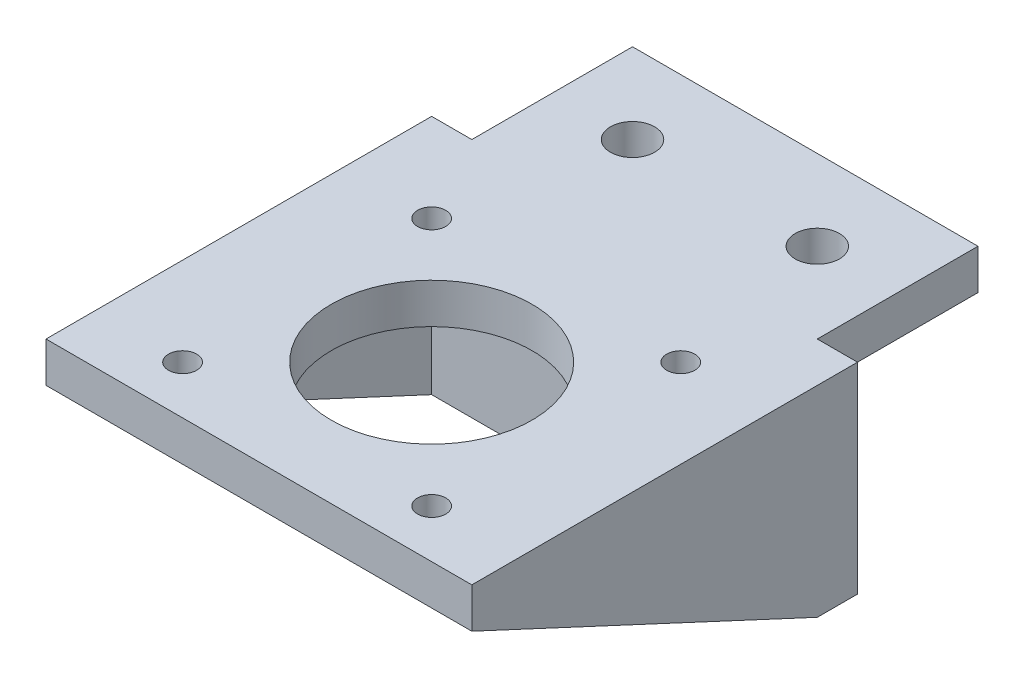
SolidWorks part; units mm, degrees
ref_plane "前视基准面" through (0, 0, 0) normal (0, 0, 1) x (1, 0, 0)
ref_plane "上视基准面" through (0, 0, 0) normal (0, 1, 0) x (1, 0, 0)
ref_plane "右视基准面" through (0, 0, 0) normal (1, 0, 0) x (0, 0, -1)
sketch "草图1" plane through (0, 0, 0) normal (0, 1, 0) x (1, 0, 0)
  line L1 (-15.1234, 10.3825) -> (27.8766, 10.3825)
  line L2 (-15.1234, 10.3825) -> (-15.1234, -32.6175)
  line L3 (-15.1234, -32.6175) -> (27.8766, -32.6175)
  line L4 (27.8766, 10.3825) -> (27.8766, -32.6175)
  line L5 (-15.1234, 10.3825) -> (27.8766, -32.6175) construction
  line L6 (-15.1234, -32.6175) -> (27.8766, 10.3825) construction
  line L11 (-9.1234, 4.3825) -> (21.8766, 4.3825) construction
  line L12 (-9.1234, 4.3825) -> (-9.1234, -26.6175) construction
  line L13 (-9.1234, -26.6175) -> (21.8766, -26.6175) construction
  line L14 (21.8766, 4.3825) -> (21.8766, -26.6175) construction
  line L15 (6.3766, -26.6175) -> (6.3766, 4.3825) construction
  line L16 (-9.1234, -11.1175) -> (21.8766, -11.1175) construction
  circle A5 centre (-9.1234, -26.6175) radius 1.75
  circle A6 centre (21.8766, -26.6175) radius 1.75
  circle A7 centre (21.8766, 4.3825) radius 1.75
  circle A8 centre (-9.1234, 4.3825) radius 1.75
  circle A9 centre (6.3766, -11.1175) radius 12.5
  point P4 (6.3766, -11.1175)
  point P5 (6.3766, -11.1175)
  point P6 (6.3766, -11.1175)
  dimension "D3" = 31
  dimension "D5" = 3.5
  dimension "D6" = 25
  dimension "D1" = 43
  dimension "D2" = 43
  dimension "D4" = 31
extrude "凸台-拉伸1" add sketch "草图1" along normal blind 5
sketch "草图2" plane through (0, 0, -10.3825) normal (0, 0, -1) x (-1, 0, 0)
  line L4 (-27.8766, 0) -> (15.1234, 0)
  line L5 (15.1234, 0) -> (15.1234, 5)
  line L6 (15.1234, 5) -> (-27.8766, 5)
  line L7 (-27.8766, 5) -> (-27.8766, 0)
  line L8 (-27.8766, 0) -> (15.1234, 0)
  line L9 (15.1234, 0) -> (15.1234, 5)
  line L10 (15.1234, 5) -> (-27.8766, 5)
  line L11 (-27.8766, 5) -> (-27.8766, 0)
  dimension "D1" = 0
extrude "凸台-拉伸2" add sketch "草图2" along normal blind 25
sketch "草图3" plane through (0, 0, 0) normal (0, -1, 0) x (1, 0, 0)
  line L0 (-15.1234, -35.3825) -> (-15.1234, 32.6175) construction
  line L1 (-15.1234, -10.3825) -> (27.8766, -10.3825)
  line L2 (-15.1234, -10.3825) -> (-15.1234, -15.3825)
  line L3 (-15.1234, -15.3825) -> (27.8766, -15.3825)
  line L4 (27.8766, -10.3825) -> (27.8766, -15.3825)
  line L5 (-15.1234, -10.3825) -> (27.8766, -15.3825) construction
  line L6 (-15.1234, -15.3825) -> (27.8766, -10.3825) construction
  line L7 (27.8766, 32.6175) -> (27.8766, -35.3825) construction
  line L8 (27.8766, -35.3825) -> (-15.1234, -35.3825) construction
  point P4 (6.3766, -12.8825)
  dimension "D1" = 20
  dimension "D2" = 5
extrude "凸台-拉伸3" add sketch "草图3" along normal blind 20
sketch "草图4" plane through (27.8766, 0, 0) normal (1, 0, 0) x (0, 0, -1)
  line L0 (-32.6175, 0) -> (10.3825, -20)
  line L1 (10.3825, -20) -> (15.3825, -20)
  line L2 (15.3825, -20) -> (15.3825, 5)
  line L3 (-32.6175, 5) -> (35.3825, 5) construction
  line L4 (15.3825, 5) -> (-32.6175, 5)
  line L5 (-32.6175, 5) -> (-32.6175, 0)
extrude "凸台-拉伸4" add sketch "草图4" along normal blind 5
sketch "草图9" plane through (-15.1234, 0, 0) normal (-1, 0, 0) x (0, 0, 1)
  line L0 (32.6175, 5) -> (32.6175, 0)
  line L5 (-10.3825, -20) -> (-15.3825, -20)
  line L6 (-15.3825, -20) -> (-15.3825, 5)
  line L7 (-35.3825, 5) -> (32.6175, 5) construction
  line L8 (-15.3825, 5) -> (32.6175, 5)
  line L10 (32.6175, 0) -> (-10.3825, -20)
extrude "凸台-拉伸6" add sketch "草图9" along normal blind 5
sketch "草图10" plane through (0, 5, 0) normal (0, 1, 0) x (1, 0, 0)
  line L0 (-15.1234, 25.3825) -> (27.8766, 25.3825) construction
  line L1 (-15.1234, 35.3825) -> (-15.1234, 15.3825) construction
  line L2 (27.8766, 15.3825) -> (27.8766, 35.3825) construction
  circle A0 centre (-5.1234, 25.3825) radius 2.75
  circle A1 centre (17.8766, 25.3825) radius 2.75
  dimension "D1" = 5.5
  dimension "D2" = 5.5
  dimension "D3" = 10
  dimension "D4" = 10
extrude "切除-拉伸1" cut sketch "草图10" against normal through all
